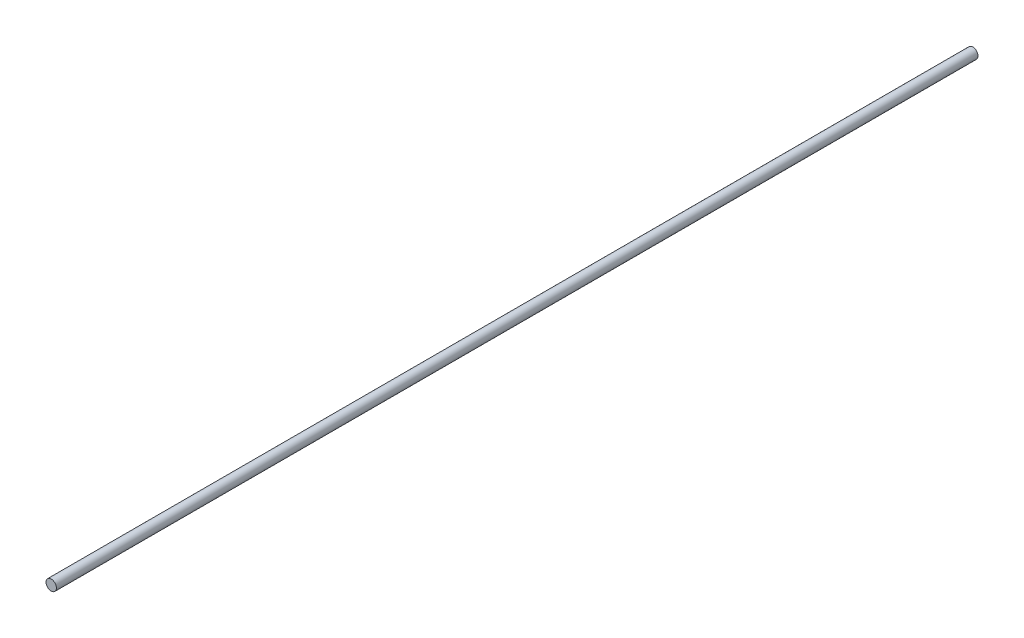
SolidWorks part; units mm, degrees
material "AISI 1020"
ref_plane "Front Plane" through (0, 0, 0) normal (0, 0, 1) x (1, 0, 0)
ref_plane "Top Plane" through (0, 0, 0) normal (0, 1, 0) x (1, 0, 0)
ref_plane "Right Plane" through (0, 0, 0) normal (1, 0, 0) x (0, 0, -1)
sketch "Sketch1" plane through (0, 0, 0) normal (0, 0, 1) x (1, 0, 0)
  circle A0 centre (0, 0) radius 7.9375
  dimension "D1" = 15.875
extrude "Boss-Extrude1" add sketch "Sketch1" along normal blind 2254.25
sketch "Sketch2" plane through (0, 0, 0) normal (0, 0, -1) x (-1, 0, 0)
  circle A0 centre (0, 0) radius 7.9375
extrude "Cut-Extrude1" cut sketch "Sketch2" against normal blind 596.9
sketch "Sketch3" plane through (0, 0, 2254.25) normal (0, 0, 1) x (1, 0, 0)
  circle A0 centre (0, 0) radius 7.9375
extrude "Cut-Extrude2" cut sketch "Sketch3" against normal blind 254
